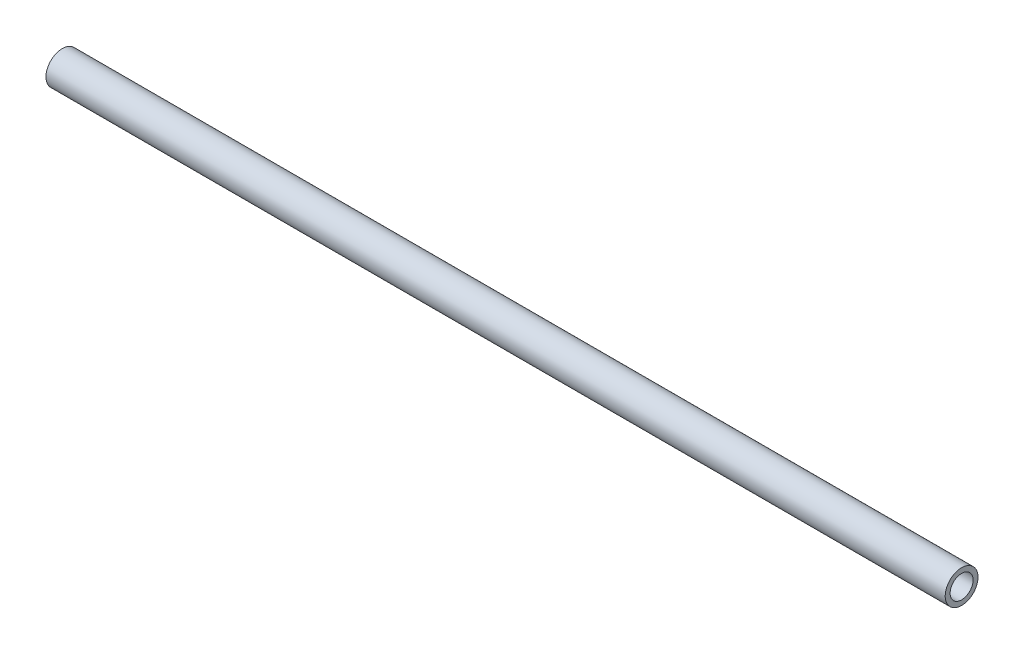
SolidWorks part; units mm, degrees
material "AISI 4130 Steel, annealed at 865C"
ref_plane "Front Plane" through (0, 0, 0) normal (0, 0, 1) x (1, 0, 0)
ref_plane "Top Plane" through (0, 0, 0) normal (0, 1, 0) x (1, 0, 0)
ref_plane "Right Plane" through (0, 0, 0) normal (1, 0, 0) x (0, 0, -1)
sketch "Sketch1" plane through (0, 0, 0) normal (0, 0, 1) x (1, 0, 0)
  line L0 (265.225, 0) -> (-265.225, 0) construction
  line L2 (-274.2476, 10) -> (274.2476, 10)
  line L4 (-274.2476, 10) -> (-274.2476, 7)
  line L5 (-274.2476, 7) -> (274.2476, 7)
  line L6 (274.2476, 7) -> (274.2476, 10)
  line L7 (0, 0) -> (0, 10) construction
  point P4 (0, 0)
  point P9 (0, 7)
  point P14 (305.9693, 0)
  point P15 (-305.9693, 0)
  dimension "D2" = 20
  dimension "D1" = 14
  dimension "D3" = 611.9386
  dimension "D4" = 31.7217
revolve "Revolve1" add sketch "Sketch1" angle 360 about L0
equation "\"CA_ID\"= 14"
equation "\"D1@Sketch1\"=\"CA_ID\""
equation "\"tube_end_to_ball_center\" = 31.721675mm"
equation "\"D4@Sketch1\"=\"tube_end_to_ball_center\""
